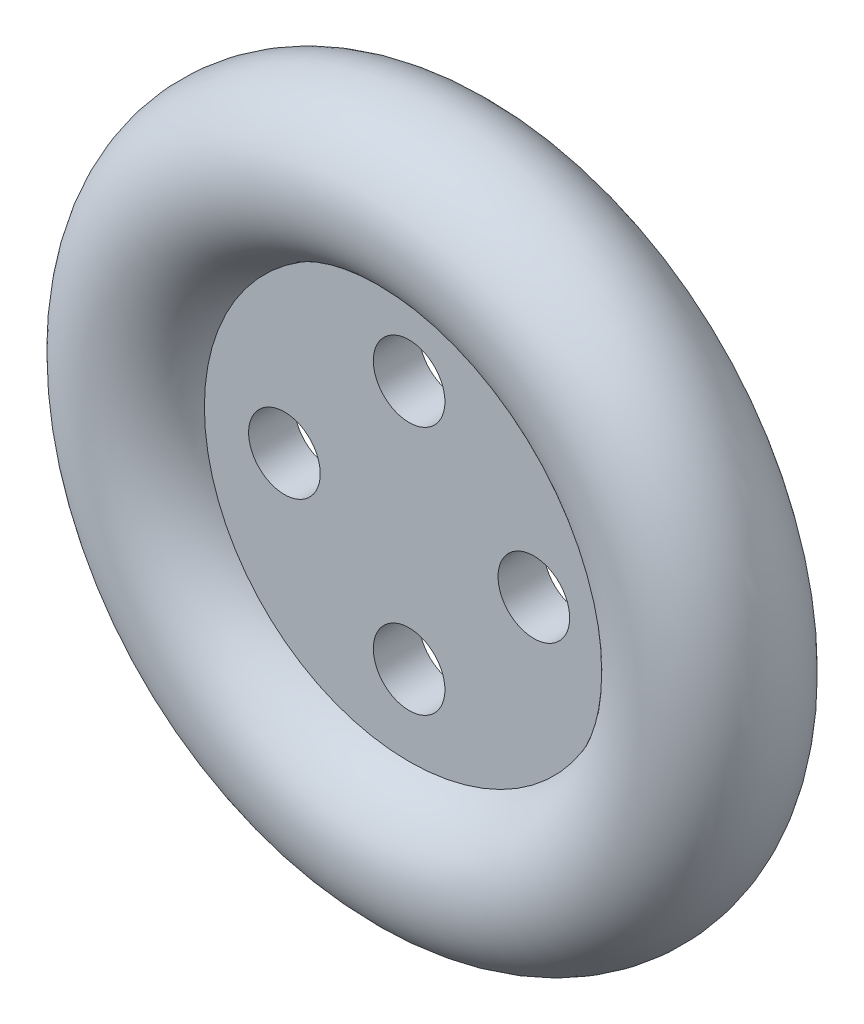
SolidWorks part; units mm, degrees
ref_plane "前视基准面" through (0, 0, 0) normal (0, 0, 1) x (1, 0, 0)
ref_plane "上视基准面" through (0, 0, 0) normal (0, 1, 0) x (1, 0, 0)
ref_plane "右视基准面" through (0, 0, 0) normal (1, 0, 0) x (0, 0, -1)
sketch "草图2" plane through (0, 0, 0) normal (0, 0, 1) x (1, 0, 0)
  circle A0 centre (0, 0) radius 60.5025
  circle A1 centre (0, 0) radius 70.4498
extrude "凸台-拉伸1" add sketch "草图2" along normal blind 10 contours A0
sketch "草图3" plane through (0, 0, 0) normal (0, 1, 0) x (1, 0, 0)
  line L0 (-60.5025, 0) -> (-60.5025, -10) construction
  line L1 (0, 0) -> (0, -10)
  line L2 (-60.5025, -10) -> (60.5025, -10) construction
  circle A0 centre (-60.5025, -5) radius 6.6313
revolve "旋转-薄壁1" add sketch "草图3" angle 360 about L1
sketch "草图4" plane through (0, 0, 0) normal (0, 0, 1) x (1, 0, 0)
  circle A0 centre (0, 27.1893) radius 7.8091
  circle A1 centre (27.1893, 0) radius 7.8091
  circle A2 centre (0, -27.1893) radius 7.8091
  circle A3 centre (-27.1893, 0) radius 7.8091
  point P11 (0, 0)
  dimension "D1" = 4
extrude "切除-拉伸1" cut sketch "草图4" along normal blind 49
